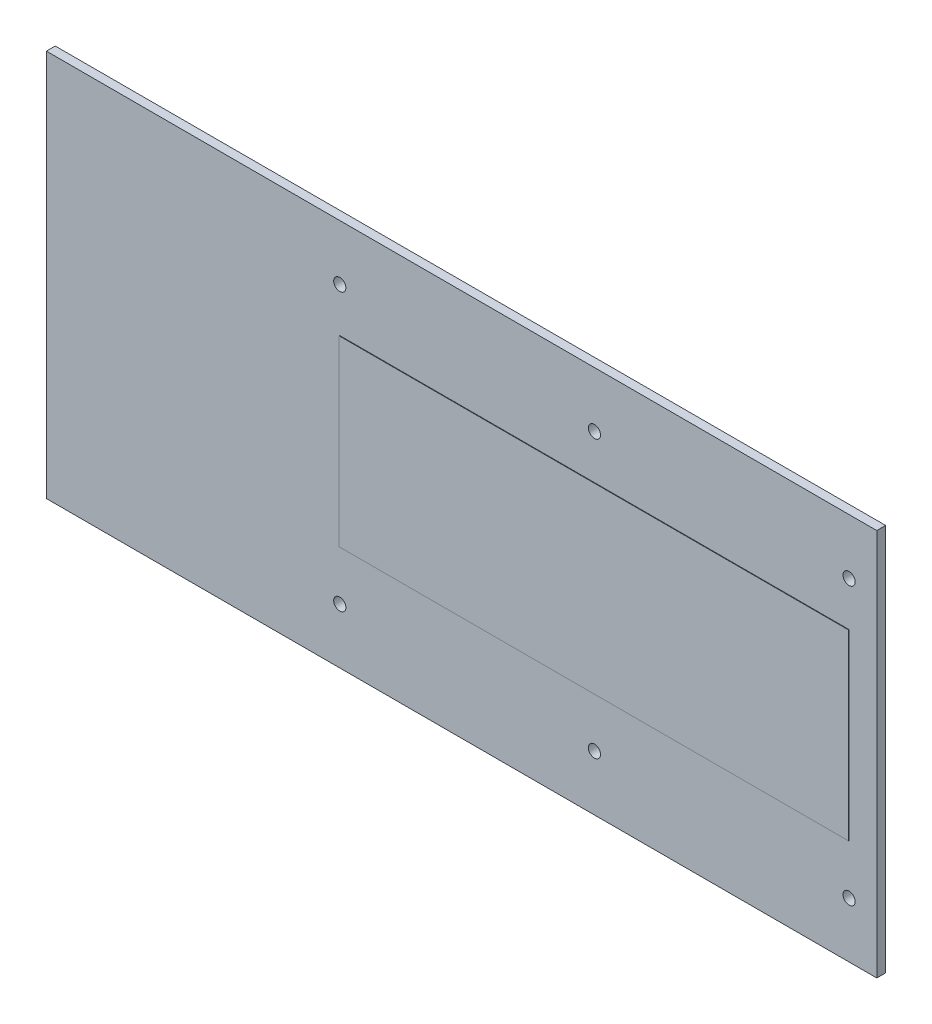
SolidWorks part; units mm, degrees
ref_plane "Front Plane" through (0, 0, 0) normal (0, 0, 1) x (1, 0, 0)
ref_plane "Top Plane" through (0, 0, 0) normal (0, 1, 0) x (1, 0, 0)
ref_plane "Right Plane" through (0, 0, 0) normal (1, 0, 0) x (0, 0, -1)
curve "ImportedCurve1"
curve "ImportedCurve2"
curve "ImportedCurve3"
curve "ImportedCurve4"
curve "ImportedCurve5"
curve "ImportedCurve6"
curve "ImportedCurve7"
curve "ImportedCurve8"
curve "ImportedCurve9"
curve "ImportedCurve10"
curve "ImportedCurve11"
curve "ImportedCurve12"
curve "ImportedCurve13"
curve "ImportedCurve14"
curve "ImportedCurve15"
curve "ImportedCurve16"
curve "ImportedCurve17"
curve "ImportedCurve18"
curve "ImportedCurve19"
curve "ImportedCurve20"
curve "ImportedCurve21"
curve "ImportedCurve22"
curve "ImportedCurve23"
curve "ImportedCurve24"
curve "ImportedCurve25"
curve "ImportedCurve26"
curve "ImportedCurve27"
curve "ImportedCurve28"
curve "ImportedCurve29"
curve "ImportedCurve30"
curve "ImportedCurve31"
curve "ImportedCurve32"
curve "ImportedCurve33"
curve "ImportedCurve34"
curve "ImportedCurve35"
curve "ImportedCurve36"
curve "ImportedCurve37"
curve "ImportedCurve38"
curve "ImportedCurve39"
curve "ImportedCurve40"
curve "ImportedCurve41"
curve "ImportedCurve42"
curve "ImportedCurve43"
curve "ImportedCurve44"
curve "ImportedCurve45"
curve "ImportedCurve46"
curve "ImportedCurve47"
curve "ImportedCurve48"
curve "ImportedCurve49"
curve "ImportedCurve50"
curve "ImportedCurve51"
curve "ImportedCurve52"
curve "ImportedCurve53"
curve "ImportedCurve54"
curve "ImportedCurve55"
curve "ImportedCurve56"
curve "ImportedCurve57"
curve "ImportedCurve58"
curve "ImportedCurve59"
curve "ImportedCurve60"
curve "ImportedCurve61"
curve "ImportedCurve62"
curve "ImportedCurve63"
curve "ImportedCurve64"
curve "ImportedCurve65"
curve "ImportedCurve66"
curve "ImportedCurve67"
curve "ImportedCurve68"
curve "ImportedCurve69"
curve "ImportedCurve70"
curve "ImportedCurve71"
curve "ImportedCurve72"
curve "ImportedCurve73"
curve "ImportedCurve74"
curve "ImportedCurve75"
curve "ImportedCurve76"
curve "ImportedCurve77"
curve "ImportedCurve78"
curve "ImportedCurve79"
curve "ImportedCurve80"
curve "ImportedCurve81"
curve "ImportedCurve82"
curve "ImportedCurve83"
curve "ImportedCurve84"
curve "ImportedCurve85"
curve "ImportedCurve86"
curve "ImportedCurve87"
curve "ImportedCurve88"
curve "ImportedCurve89"
curve "ImportedCurve90"
curve "ImportedCurve91"
curve "ImportedCurve92"
curve "ImportedCurve93"
curve "ImportedCurve94"
curve "ImportedCurve95"
curve "ImportedCurve96"
curve "ImportedCurve97"
curve "ImportedCurve98"
curve "ImportedCurve99"
curve "ImportedCurve100"
curve "ImportedCurve101"
curve "ImportedCurve102"
curve "ImportedCurve103"
curve "ImportedCurve104"
curve "ImportedCurve105"
curve "ImportedCurve106"
curve "ImportedCurve107"
curve "ImportedCurve108"
curve "ImportedCurve109"
curve "ImportedCurve110"
curve "ImportedCurve111"
curve "ImportedCurve112"
curve "ImportedCurve113"
curve "ImportedCurve114"
curve "ImportedCurve115"
curve "ImportedCurve116"
curve "ImportedCurve117"
curve "ImportedCurve118"
curve "ImportedCurve119"
curve "ImportedCurve120"
curve "ImportedCurve121"
curve "ImportedCurve122"
curve "ImportedCurve123"
curve "ImportedCurve124"
curve "ImportedCurve125"
curve "ImportedCurve126"
curve "ImportedCurve127"
curve "ImportedCurve128"
curve "ImportedCurve129"
curve "ImportedCurve130"
curve "ImportedCurve131"
curve "ImportedCurve132"
curve "ImportedCurve133"
curve "ImportedCurve134"
curve "ImportedCurve135"
curve "ImportedCurve136"
curve "ImportedCurve137"
curve "ImportedCurve138"
curve "ImportedCurve139"
curve "ImportedCurve140"
curve "ImportedCurve141"
curve "ImportedCurve142"
curve "ImportedCurve143"
curve "ImportedCurve144"
curve "ImportedCurve145"
curve "ImportedCurve146"
curve "ImportedCurve147"
curve "ImportedCurve148"
curve "ImportedCurve149"
curve "ImportedCurve150"
curve "ImportedCurve151"
curve "ImportedCurve152"
curve "ImportedCurve153"
curve "ImportedCurve154"
curve "ImportedCurve155"
curve "ImportedCurve156"
curve "ImportedCurve157"
curve "ImportedCurve158"
curve "ImportedCurve159"
curve "ImportedCurve160"
curve "ImportedCurve161"
curve "ImportedCurve162"
curve "ImportedCurve163"
curve "ImportedCurve164"
curve "ImportedCurve165"
curve "ImportedCurve166"
curve "ImportedCurve167"
curve "ImportedCurve168"
curve "ImportedCurve169"
curve "ImportedCurve170"
curve "ImportedCurve171"
curve "ImportedCurve172"
curve "ImportedCurve173"
curve "ImportedCurve174"
curve "ImportedCurve175"
curve "ImportedCurve176"
curve "ImportedCurve177"
curve "ImportedCurve178"
curve "ImportedCurve179"
curve "ImportedCurve180"
curve "ImportedCurve181"
curve "ImportedCurve182"
curve "ImportedCurve183"
curve "ImportedCurve184"
curve "ImportedCurve185"
curve "ImportedCurve186"
curve "ImportedCurve187"
curve "ImportedCurve188"
curve "ImportedCurve189"
curve "ImportedCurve190"
curve "ImportedCurve191"
curve "ImportedCurve192"
curve "ImportedCurve193"
curve "ImportedCurve194"
curve "ImportedCurve195"
curve "ImportedCurve196"
curve "ImportedCurve197"
curve "ImportedCurve198"
curve "ImportedCurve199"
curve "ImportedCurve200"
curve "ImportedCurve201"
curve "ImportedCurve202"
curve "ImportedCurve203"
curve "ImportedCurve204"
curve "ImportedCurve205"
curve "ImportedCurve206"
curve "ImportedCurve207"
curve "ImportedCurve208"
curve "ImportedCurve209"
curve "ImportedCurve210"
curve "ImportedCurve211"
curve "ImportedCurve212"
curve "ImportedCurve213"
curve "ImportedCurve214"
curve "ImportedCurve215"
curve "ImportedCurve216"
curve "ImportedCurve217"
curve "ImportedCurve218"
curve "ImportedCurve219"
curve "ImportedCurve220"
curve "ImportedCurve221"
curve "ImportedCurve222"
curve "ImportedCurve223"
curve "ImportedCurve224"
curve "ImportedCurve225"
curve "ImportedCurve226"
curve "ImportedCurve227"
curve "ImportedCurve228"
curve "ImportedCurve229"
curve "ImportedCurve230"
curve "ImportedCurve231"
curve "ImportedCurve232"
curve "ImportedCurve233"
curve "ImportedCurve234"
curve "ImportedCurve235"
curve "ImportedCurve236"
curve "ImportedCurve237"
curve "ImportedCurve238"
curve "ImportedCurve239"
curve "ImportedCurve240"
curve "ImportedCurve241"
curve "ImportedCurve242"
curve "ImportedCurve243"
curve "ImportedCurve244"
curve "ImportedCurve245"
curve "ImportedCurve246"
curve "ImportedCurve247"
curve "ImportedCurve248"
curve "ImportedCurve249"
curve "ImportedCurve250"
curve "ImportedCurve251"
curve "ImportedCurve252"
curve "ImportedCurve253"
curve "ImportedCurve254"
curve "ImportedCurve255"
curve "ImportedCurve256"
curve "ImportedCurve257"
curve "ImportedCurve258"
curve "ImportedCurve259"
curve "ImportedCurve260"
curve "ImportedCurve261"
curve "ImportedCurve262"
curve "ImportedCurve263"
curve "ImportedCurve264"
curve "ImportedCurve265"
curve "ImportedCurve266"
curve "ImportedCurve267"
curve "ImportedCurve268"
curve "ImportedCurve269"
curve "ImportedCurve270"
curve "ImportedCurve271"
curve "ImportedCurve272"
curve "ImportedCurve273"
curve "ImportedCurve274"
curve "ImportedCurve275"
curve "ImportedCurve276"
curve "ImportedCurve277"
curve "ImportedCurve278"
curve "ImportedCurve279"
curve "ImportedCurve280"
curve "ImportedCurve281"
curve "ImportedCurve282"
curve "ImportedCurve283"
curve "ImportedCurve284"
curve "ImportedCurve285"
curve "ImportedCurve286"
curve "ImportedCurve287"
curve "ImportedCurve288"
curve "ImportedCurve289"
curve "ImportedCurve290"
curve "ImportedCurve291"
curve "ImportedCurve292"
curve "ImportedCurve293"
curve "ImportedCurve294"
curve "ImportedCurve295"
curve "ImportedCurve296"
curve "ImportedCurve297"
curve "ImportedCurve298"
curve "ImportedCurve299"
curve "ImportedCurve300"
curve "ImportedCurve301"
curve "ImportedCurve302"
curve "ImportedCurve303"
curve "ImportedCurve304"
curve "ImportedCurve305"
curve "ImportedCurve306"
curve "ImportedCurve307"
curve "ImportedCurve308"
curve "ImportedCurve309"
curve "ImportedCurve310"
curve "ImportedCurve311"
curve "ImportedCurve312"
curve "ImportedCurve313"
curve "ImportedCurve314"
curve "ImportedCurve315"
curve "ImportedCurve316"
curve "ImportedCurve317"
curve "ImportedCurve318"
curve "ImportedCurve319"
curve "ImportedCurve320"
curve "ImportedCurve321"
curve "ImportedCurve322"
curve "ImportedCurve323"
curve "ImportedCurve324"
curve "ImportedCurve325"
curve "ImportedCurve326"
curve "ImportedCurve327"
curve "ImportedCurve328"
curve "ImportedCurve329"
curve "ImportedCurve330"
curve "ImportedCurve331"
curve "ImportedCurve332"
curve "ImportedCurve333"
curve "ImportedCurve334"
curve "ImportedCurve335"
curve "ImportedCurve336"
curve "ImportedCurve337"
curve "ImportedCurve338"
curve "ImportedCurve339"
curve "ImportedCurve340"
curve "ImportedCurve341"
curve "ImportedCurve342"
curve "ImportedCurve343"
curve "ImportedCurve344"
curve "ImportedCurve345"
curve "ImportedCurve346"
curve "ImportedCurve347"
curve "ImportedCurve348"
curve "ImportedCurve349"
curve "ImportedCurve350"
curve "ImportedCurve351"
curve "ImportedCurve352"
curve "ImportedCurve353"
curve "ImportedCurve354"
curve "ImportedCurve355"
curve "ImportedCurve356"
curve "ImportedCurve357"
curve "ImportedCurve358"
curve "ImportedCurve359"
curve "ImportedCurve360"
curve "ImportedCurve361"
curve "ImportedCurve362"
curve "ImportedCurve363"
curve "ImportedCurve364"
curve "ImportedCurve365"
curve "ImportedCurve366"
curve "ImportedCurve367"
curve "ImportedCurve368"
curve "ImportedCurve369"
curve "ImportedCurve370"
curve "ImportedCurve371"
curve "ImportedCurve372"
curve "ImportedCurve373"
curve "ImportedCurve374"
curve "ImportedCurve375"
curve "ImportedCurve376"
curve "ImportedCurve377"
curve "ImportedCurve378"
curve "ImportedCurve379"
curve "ImportedCurve380"
curve "ImportedCurve381"
curve "ImportedCurve382"
curve "ImportedCurve383"
curve "ImportedCurve384"
curve "ImportedCurve385"
curve "ImportedCurve386"
curve "ImportedCurve387"
curve "ImportedCurve388"
curve "ImportedCurve389"
curve "ImportedCurve390"
curve "ImportedCurve391"
curve "ImportedCurve392"
curve "ImportedCurve393"
curve "ImportedCurve394"
curve "ImportedCurve395"
curve "ImportedCurve396"
curve "ImportedCurve397"
curve "ImportedCurve398"
curve "ImportedCurve399"
curve "ImportedCurve400"
curve "ImportedCurve401"
curve "ImportedCurve402"
curve "ImportedCurve403"
curve "ImportedCurve404"
curve "ImportedCurve405"
curve "ImportedCurve406"
curve "ImportedCurve407"
curve "ImportedCurve408"
curve "ImportedCurve409"
curve "ImportedCurve410"
curve "ImportedCurve411"
curve "ImportedCurve412"
curve "ImportedCurve413"
curve "ImportedCurve414"
curve "ImportedCurve415"
curve "ImportedCurve416"
curve "ImportedCurve417"
curve "ImportedCurve418"
curve "ImportedCurve419"
curve "ImportedCurve420"
curve "ImportedCurve421"
curve "ImportedCurve422"
curve "ImportedCurve423"
curve "ImportedCurve424"
curve "ImportedCurve425"
curve "ImportedCurve426"
curve "ImportedCurve427"
curve "ImportedCurve428"
curve "ImportedCurve429"
curve "ImportedCurve430"
curve "ImportedCurve431"
curve "ImportedCurve432"
curve "ImportedCurve433"
curve "ImportedCurve434"
curve "ImportedCurve435"
curve "ImportedCurve436"
curve "ImportedCurve437"
curve "ImportedCurve438"
curve "ImportedCurve439"
curve "ImportedCurve440"
curve "ImportedCurve441"
curve "ImportedCurve442"
curve "ImportedCurve443"
curve "ImportedCurve444"
curve "ImportedCurve445"
curve "ImportedCurve446"
curve "ImportedCurve447"
curve "ImportedCurve448"
curve "ImportedCurve449"
curve "ImportedCurve450"
curve "ImportedCurve451"
curve "ImportedCurve452"
curve "ImportedCurve453"
curve "ImportedCurve454"
curve "ImportedCurve455"
curve "ImportedCurve456"
curve "ImportedCurve457"
curve "ImportedCurve458"
curve "ImportedCurve459"
curve "ImportedCurve460"
curve "ImportedCurve461"
curve "ImportedCurve462"
curve "ImportedCurve463"
curve "ImportedCurve464"
curve "ImportedCurve465"
curve "ImportedCurve466"
curve "ImportedCurve467"
curve "ImportedCurve468"
curve "ImportedCurve469"
curve "ImportedCurve470"
curve "ImportedCurve471"
curve "ImportedCurve472"
curve "ImportedCurve473"
curve "ImportedCurve474"
curve "ImportedCurve475"
curve "ImportedCurve476"
curve "ImportedCurve477"
curve "ImportedCurve478"
curve "ImportedCurve479"
curve "ImportedCurve480"
curve "ImportedCurve481"
curve "ImportedCurve482"
curve "ImportedCurve483"
curve "ImportedCurve484"
curve "ImportedCurve485"
curve "ImportedCurve486"
curve "ImportedCurve487"
curve "ImportedCurve488"
curve "ImportedCurve489"
curve "ImportedCurve490"
curve "ImportedCurve491"
curve "ImportedCurve492"
curve "ImportedCurve493"
curve "ImportedCurve494"
curve "ImportedCurve495"
curve "ImportedCurve496"
curve "ImportedCurve497"
curve "ImportedCurve498"
curve "ImportedCurve499"
curve "ImportedCurve500"
curve "ImportedCurve501"
curve "ImportedCurve502"
curve "ImportedCurve503"
curve "ImportedCurve504"
curve "ImportedCurve505"
curve "ImportedCurve506"
curve "ImportedCurve507"
curve "ImportedCurve508"
curve "ImportedCurve509"
curve "ImportedCurve510"
curve "ImportedCurve511"
curve "ImportedCurve512"
curve "ImportedCurve513"
curve "ImportedCurve514"
curve "ImportedCurve515"
curve "ImportedCurve516"
curve "ImportedCurve517"
curve "ImportedCurve518"
curve "ImportedCurve519"
curve "ImportedCurve520"
curve "ImportedCurve521"
curve "ImportedCurve522"
curve "ImportedCurve523"
curve "ImportedCurve524"
curve "ImportedCurve525"
curve "ImportedCurve526"
curve "ImportedCurve527"
curve "ImportedCurve528"
curve "ImportedCurve529"
curve "ImportedCurve530"
curve "ImportedCurve531"
curve "ImportedCurve532"
curve "ImportedCurve533"
curve "ImportedCurve534"
curve "ImportedCurve535"
curve "ImportedCurve536"
curve "ImportedCurve537"
curve "ImportedCurve538"
curve "ImportedCurve539"
curve "ImportedCurve540"
curve "ImportedCurve541"
curve "ImportedCurve542"
curve "ImportedCurve543"
curve "ImportedCurve544"
curve "ImportedCurve545"
curve "ImportedCurve546"
curve "ImportedCurve547"
curve "ImportedCurve548"
curve "ImportedCurve549"
curve "ImportedCurve550"
curve "ImportedCurve551"
curve "ImportedCurve552"
curve "ImportedCurve553"
curve "ImportedCurve554"
curve "ImportedCurve555"
curve "ImportedCurve556"
curve "ImportedCurve557"
curve "ImportedCurve558"
curve "ImportedCurve559"
curve "ImportedCurve560"
curve "ImportedCurve561"
curve "ImportedCurve562"
curve "ImportedCurve563"
curve "ImportedCurve564"
curve "ImportedCurve565"
curve "ImportedCurve566"
curve "ImportedCurve567"
curve "ImportedCurve568"
curve "ImportedCurve569"
curve "ImportedCurve570"
curve "ImportedCurve571"
curve "ImportedCurve572"
curve "ImportedCurve573"
curve "ImportedCurve574"
curve "ImportedCurve575"
curve "ImportedCurve576"
curve "ImportedCurve577"
curve "ImportedCurve578"
curve "ImportedCurve579"
curve "ImportedCurve580"
curve "ImportedCurve581"
curve "ImportedCurve582"
curve "ImportedCurve583"
curve "ImportedCurve584"
curve "ImportedCurve585"
curve "ImportedCurve586"
curve "ImportedCurve587"
curve "ImportedCurve588"
curve "ImportedCurve589"
curve "ImportedCurve590"
curve "ImportedCurve591"
curve "ImportedCurve592"
curve "ImportedCurve593"
curve "ImportedCurve594"
curve "ImportedCurve595"
curve "ImportedCurve596"
curve "ImportedCurve597"
curve "ImportedCurve598"
curve "ImportedCurve599"
curve "ImportedCurve600"
curve "ImportedCurve601"
curve "ImportedCurve602"
curve "ImportedCurve603"
curve "ImportedCurve604"
curve "ImportedCurve605"
curve "ImportedCurve606"
curve "ImportedCurve607"
curve "ImportedCurve608"
curve "ImportedCurve609"
curve "ImportedCurve610"
curve "ImportedCurve611"
curve "ImportedCurve612"
curve "ImportedCurve613"
curve "ImportedCurve614"
curve "ImportedCurve615"
curve "ImportedCurve616"
curve "ImportedCurve617"
curve "ImportedCurve618"
curve "ImportedCurve619"
curve "ImportedCurve620"
curve "ImportedCurve621"
curve "ImportedCurve622"
curve "ImportedCurve623"
curve "ImportedCurve624"
curve "ImportedCurve625"
curve "ImportedCurve626"
curve "ImportedCurve627"
curve "ImportedCurve628"
curve "ImportedCurve629"
curve "ImportedCurve630"
curve "ImportedCurve631"
curve "ImportedCurve632"
curve "ImportedCurve633"
curve "ImportedCurve634"
curve "ImportedCurve635"
curve "ImportedCurve636"
curve "ImportedCurve637"
curve "ImportedCurve638"
curve "ImportedCurve639"
curve "ImportedCurve640"
curve "ImportedCurve641"
curve "ImportedCurve642"
curve "ImportedCurve643"
curve "ImportedCurve644"
curve "ImportedCurve645"
curve "ImportedCurve646"
curve "ImportedCurve647"
curve "ImportedCurve648"
curve "ImportedCurve649"
curve "ImportedCurve650"
curve "ImportedCurve651"
curve "ImportedCurve652"
curve "ImportedCurve653"
curve "ImportedCurve654"
curve "ImportedCurve655"
curve "ImportedCurve656"
curve "ImportedCurve657"
curve "ImportedCurve658"
curve "ImportedCurve659"
curve "ImportedCurve660"
curve "ImportedCurve661"
curve "ImportedCurve662"
curve "ImportedCurve663"
sketch "Sketch1" plane through (0, 0, 0) normal (0, 0, 1) x (1, 0, 0)
  line L0 (48, 70) -> (150, 70) construction
  line L1 (150, 70) -> (150, 0) construction
  line L2 (0, 0) -> (0, 18.6) construction
  line L3 (48, 0) -> (46, 0) construction
  line L4 (150, 0) -> (48, 0) construction
  line L5 (46, 0) -> (0, 0) construction
  line L6 (0, 18.6) -> (0, 36) construction
  line L7 (0, 36) -> (0, 47) construction
  line L8 (0, 47) -> (0, 70) construction
  line L9 (0, 70) -> (48, 70) construction
  line L10 (48, 70) -> (150, 70)
  line L11 (150, 70) -> (150, 0)
  line L12 (0, 0) -> (0, 18.6)
  line L13 (48, 0) -> (46, 0)
  line L14 (150, 0) -> (48, 0)
  line L15 (46, 0) -> (0, 0)
  line L16 (0, 18.6) -> (0, 36)
  line L17 (0, 36) -> (0, 47)
  line L18 (0, 47) -> (0, 70)
  line L19 (0, 70) -> (48, 70)
  line L20 (9, 36) -> (0, 36) construction
  line L21 (0, 47) -> (9, 47) construction
  line L22 (9, 47) -> (9, 36) construction
  line L23 (46, 18.6) -> (46, 0) construction
  line L24 (46, 18.6) -> (0, 18.6) construction
  line L25 (48, 0) -> (48, 70) construction
  line L26 (145, 19) -> (145, 52) construction
  line L27 (53, 19) -> (145, 19) construction
  line L28 (53, 52) -> (53, 19) construction
  line L29 (145, 52) -> (53, 52) construction
  line L30 (9, 36) -> (0, 36) construction
  line L31 (0, 47) -> (9, 47) construction
  line L32 (9, 47) -> (9, 36) construction
  line L33 (46, 18.6) -> (46, 0) construction
  line L34 (46, 18.6) -> (0, 18.6) construction
  line L35 (48, 0) -> (48, 70) construction
  line L36 (145, 19) -> (145, 52)
  line L37 (53, 19) -> (145, 19)
  line L38 (53, 52) -> (53, 19)
  line L39 (145, 52) -> (53, 52)
  arc A0 (99, 11.1) -> (99, 8.9) centre (99, 10) ccw construction
  arc A1 (99, 8.9) -> (99, 11.1) centre (99, 10) ccw construction
  arc A2 (99, 61.1) -> (99, 58.9) centre (99, 60) ccw construction
  arc A3 (99, 58.9) -> (99, 61.1) centre (99, 60) ccw construction
  arc A4 (53, 61.1) -> (53, 58.9) centre (53, 60) ccw construction
  arc A5 (53, 58.9) -> (53, 61.1) centre (53, 60) ccw construction
  arc A6 (99, 11.1) -> (99, 8.9) centre (99, 10) ccw
  arc A7 (99, 8.9) -> (99, 11.1) centre (99, 10) ccw
  arc A8 (99, 61.1) -> (99, 58.9) centre (99, 60) ccw
  arc A9 (99, 58.9) -> (99, 61.1) centre (99, 60) ccw
  arc A10 (53, 61.1) -> (53, 58.9) centre (53, 60) ccw
  arc A11 (53, 58.9) -> (53, 61.1) centre (53, 60) ccw
  arc A12 (53, 11.1) -> (53, 8.9) centre (53, 10) ccw construction
  arc A13 (53, 8.9) -> (53, 11.1) centre (53, 10) ccw construction
  arc A14 (145, 11.1) -> (145, 8.9) centre (145, 10) ccw construction
  arc A15 (145, 8.9) -> (145, 11.1) centre (145, 10) ccw construction
  arc A16 (145, 61.1) -> (145, 58.9) centre (145, 60) ccw construction
  arc A17 (145, 58.9) -> (145, 61.1) centre (145, 60) ccw construction
  arc A18 (53, 11.1) -> (53, 8.9) centre (53, 10) ccw
  arc A19 (53, 8.9) -> (53, 11.1) centre (53, 10) ccw
  arc A20 (145, 11.1) -> (145, 8.9) centre (145, 10) ccw
  arc A21 (145, 8.9) -> (145, 11.1) centre (145, 10) ccw
  arc A22 (145, 61.1) -> (145, 58.9) centre (145, 60) ccw
  arc A23 (145, 58.9) -> (145, 61.1) centre (145, 60) ccw
extrude "Boss-Extrude1" add sketch "Sketch1" along normal blind 1.6
sketch "Sketch2" plane through (0, 0, 1.6) normal (0, 0, 1) x (1, 0, 0)
  line L1 (53, 52) -> (145, 52)
  line L2 (53, 52) -> (53, 19)
  line L3 (53, 19) -> (145, 19)
  line L4 (145, 52) -> (145, 19)
extrude "Boss-Extrude2" add sketch "Sketch2" along normal blind 0.1
